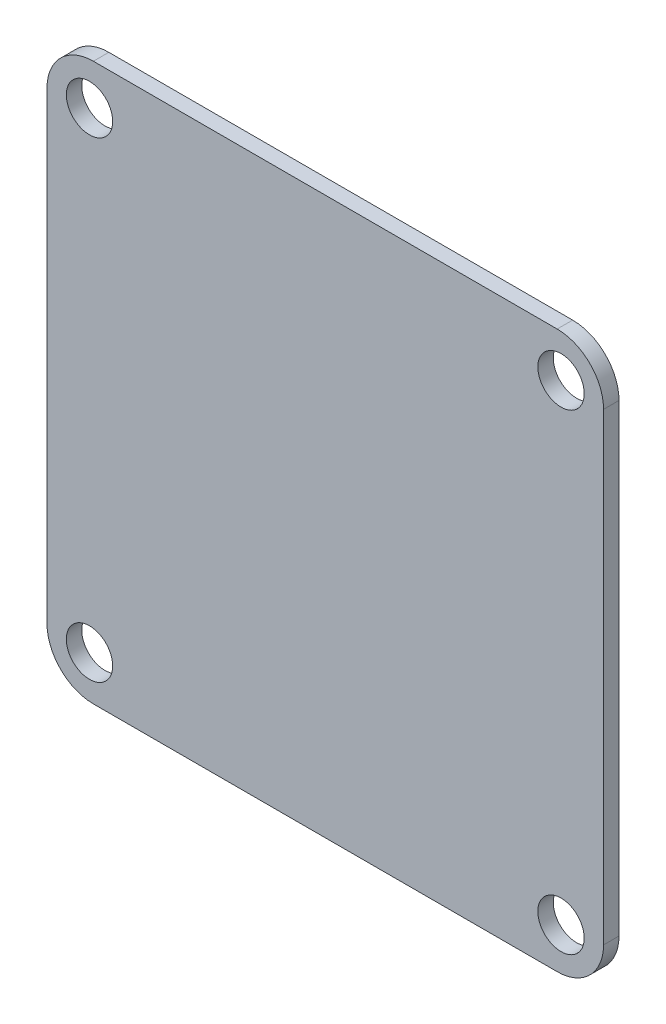
SolidWorks part; units mm, degrees
ref_plane "前视基准面" through (0, 0, 0) normal (0, 0, 1) x (1, 0, 0)
ref_plane "上视基准面" through (0, 0, 0) normal (0, 1, 0) x (1, 0, 0)
ref_plane "右视基准面" through (0, 0, 0) normal (1, 0, 0) x (0, 0, -1)
other "Configuration Table"
sketch "草图1" plane through (0, 0, 0) normal (0, 0, 1) x (1, 0, 0)
  line L1 (18, -18) -> (-18, -18)
  line L2 (18, -18) -> (18, 18)
  line L3 (18, 18) -> (-18, 18)
  line L4 (-18, -18) -> (-18, 18)
  line L5 (18, -18) -> (-18, 18) construction
  line L6 (18, 18) -> (-18, -18) construction
  point P0 (0, 0)
  dimension "D1" = 36
  dimension "D2" = 36
extrude "凸台-拉伸1" add sketch "草图1" along normal blind 1
fillet "圆角1" radius 3 4 edges at (-18, -18, 0.5) (18, -18, 0.5) (18, 18, 0.5) (-18, 18, 0.5)
sketch "草图2" plane through (0, 0, 1) normal (0, 0, 1) x (1, 0, 0)
  line L1 (15.25, -15.25) -> (-15.25, -15.25) construction
  line L2 (15.25, -15.25) -> (15.25, 15.25) construction
  line L3 (15.25, 15.25) -> (-15.25, 15.25) construction
  line L4 (-15.25, -15.25) -> (-15.25, 15.25) construction
  line L5 (15.25, -15.25) -> (-15.25, 15.25) construction
  line L6 (15.25, 15.25) -> (-15.25, -15.25) construction
  circle A0 centre (-15.25, 15.25) radius 1.5
  circle A1 centre (15.25, 15.25) radius 1.5
  circle A2 centre (15.25, -15.25) radius 1.5
  circle A3 centre (-15.25, -15.25) radius 1.5
  point P0 (0, 0)
  dimension "D3" = 3
  dimension "D4" = 3
  dimension "D5" = 3
  dimension "D6" = 3
  dimension "D1" = 30.5
  dimension "D2" = 30.5
extrude "切除-拉伸1" cut sketch "草图2" against normal blind 1
